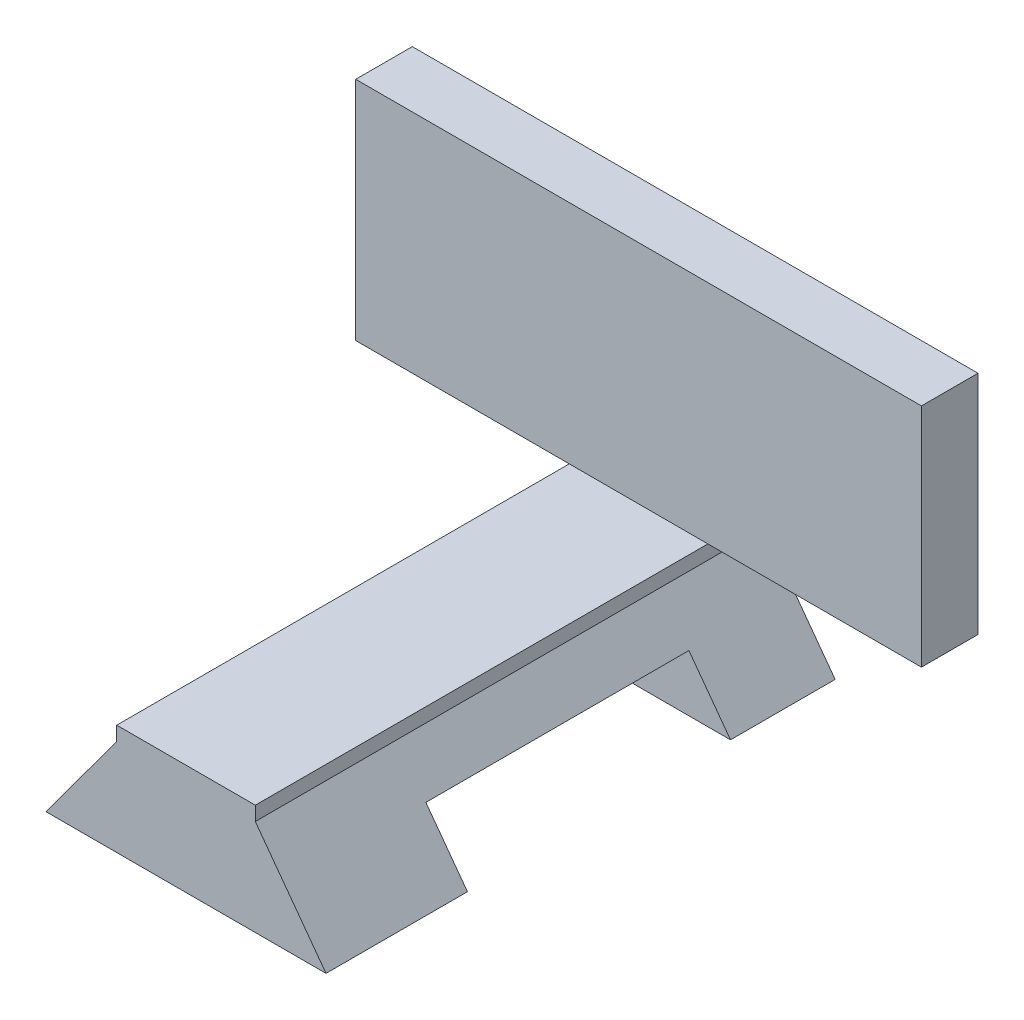
SolidWorks part; units mm, degrees
ref_plane "Front Plane" through (0, 0, 0) normal (0, 0, 1) x (1, 0, 0)
ref_plane "Top Plane" through (0, 0, 0) normal (0, 1, 0) x (1, 0, 0)
ref_plane "Right Plane" through (0, 0, 0) normal (1, 0, 0) x (0, 0, -1)
sketch "Sketch1" plane through (0, 0, 0) normal (0, 0, 1) x (1, 0, 0)
  line L1 (0, 0) -> (0, -3.4) construction
  line L2 (-4.95, -3.4) -> (4.95, -3.4)
  line L3 (-2.45, 0) -> (-4.95, -3.4)
  line L4 (2.45, 0) -> (4.95, -3.4)
  line L7 (-2.45, 0) -> (-2.45, 0.5)
  line L8 (-2.45, 0.5) -> (2.45, 0.5)
  line L9 (2.45, 0) -> (2.45, 0.5)
  point P4 (0, 0)
  point P10 (0, -3.4)
  dimension "D1" = 3.4
  dimension "D2" = 4.9
  dimension "D3" = 9.9
  dimension "D4" = 0.5
extrude "Boss-Extrude1" add sketch "Sketch1" along normal blind 18
sketch "Sketch2" plane through (0, 0, 0) normal (0, 0, -1) x (-1, 0, 0)
  line L9 (10, 0.5) -> (-10, 0.5)
  line L10 (10, 0.5) -> (10, 8.5)
  line L11 (10, 8.5) -> (-10, 8.5)
  line L12 (-10, 0.5) -> (-10, 8.5)
  line L15 (-2.45, 0.5) -> (2.45, 0.5) construction
  dimension "D1" = 8
  dimension "D2" = 8
  dimension "D3" = 20
extrude "Boss-Extrude2" add sketch "Sketch2" against normal blind 2
sketch "Sketch3" plane through (0, 0, 0) normal (1, 0, 0) x (0, 0, -1)
  line L0 (-18, -3.4) -> (-18, 0) construction
  line L1 (-13, -3.4) -> (-3.7, -3.4)
  line L2 (-13, -3.4) -> (-13, -1.4)
  line L3 (-13, -1.4) -> (-3.7, -1.4)
  line L4 (-3.7, -3.4) -> (-3.7, -1.4)
  line L5 (-18, -3.4) -> (0, -3.4) construction
  dimension "D1" = 5
  dimension "D2" = 9.3
  dimension "D3" = 2
  dimension "D4" = 0
extrude "Cut-Extrude1" cut sketch "Sketch3" against normal through all both and the other way through all
sketch "Sketch4" plane through (0, 0, 0) normal (0, 0, -1) x (-1, 0, 0)
  line L0 (0, -3.4) -> (0, 8.5) construction
  line L1 (4.95, -3.4) -> (-4.95, -3.4) construction
  line L2 (10, 8.5) -> (-10, 8.5) construction
  line L3 (-2.45, 0.5) -> (-10, 0.5) construction
  circle A0 centre (-6.2, 3) radius 1.4
  circle A1 centre (6.2, 3) radius 1.4
  dimension "D2" = 2.5
  dimension "D1" = 6.2
extrude "Boss-Extrude3" add sketch "Sketch4" along normal blind 2
fillet "Fillet1" radius 0.5 2 edges at (-4.8, 3, -2) (4.8, 3, -2)
